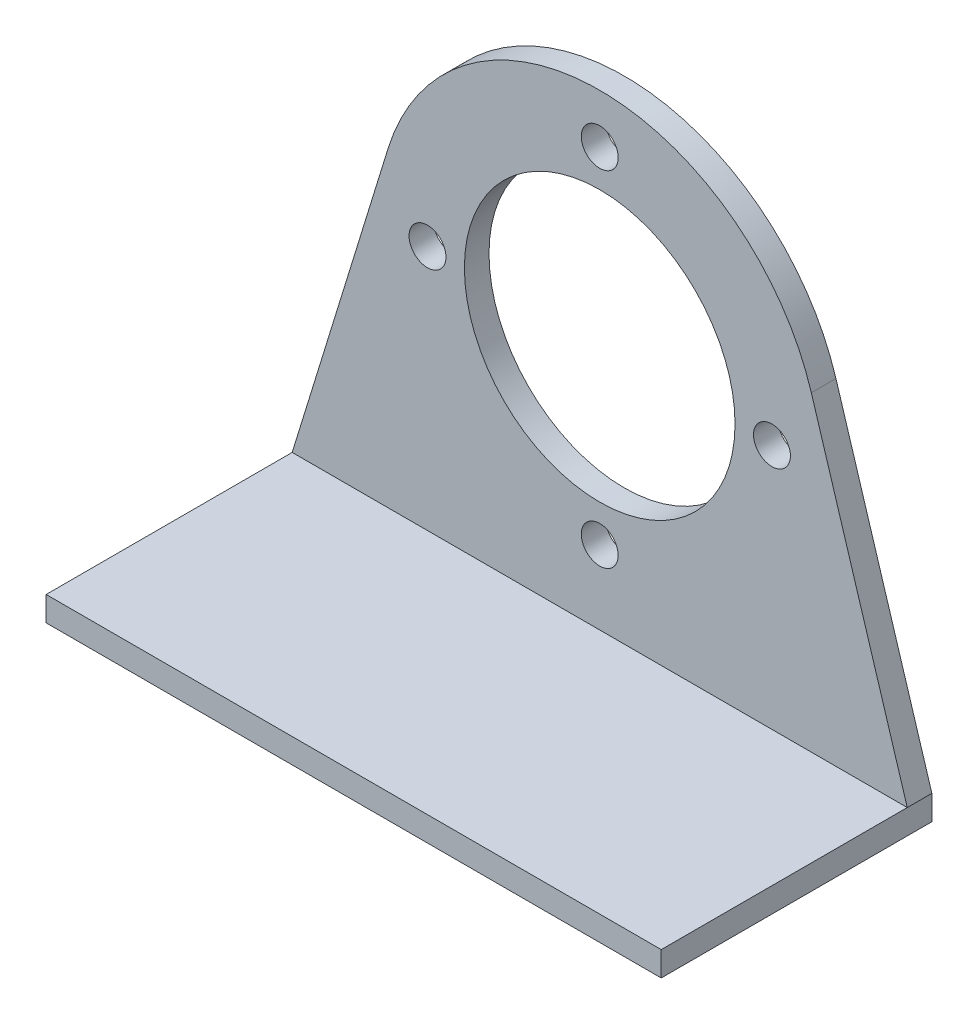
SolidWorks part; units mm, degrees
ref_plane "Front Plane" through (0, 0, 0) normal (0, 0, 1) x (1, 0, 0)
ref_plane "Top Plane" through (0, 0, 0) normal (0, 1, 0) x (1, 0, 0)
ref_plane "Right Plane" through (0, 0, 0) normal (1, 0, 0) x (0, 0, -1)
sketch "Sketch1" plane through (0, 0, 0) normal (0, 0, 1) x (1, 0, 0)
  line L0 (-25, -20) -> (25, -20)
  line L1 (-17.2015, 5.3018) -> (-25, -20)
  line L2 (17.2015, 5.3018) -> (25, -20)
  circle A0 centre (0, 0) radius 11
  circle A1 centre (0, 14) radius 1.5
  circle A2 centre (14, 0) radius 1.5
  circle A3 centre (0, -14) radius 1.5
  circle A4 centre (-14, 0) radius 1.5
  arc A6 (-17.2015, 5.3018) -> (17.2015, 5.3018) centre (0, 0) cw
  point P7 (0, -20)
  point P14 (0, 0)
  point P17 (0, 0)
  point P18 (0, 0)
  dimension "D1" = 22
  dimension "D4" = 3
  dimension "D5" = 18
  dimension "D2" = 14
  dimension "D6" = 50
  dimension "D7" = 20
  dimension "D3" = 4
extrude "Boss-Extrude1" add sketch "Sketch1" along normal blind 2
sketch "Sketch2" plane through (0, 0, 2) normal (0, 0, 1) x (1, 0, 0)
  line L1 (-25, -20) -> (25, -20)
  line L2 (-25, -20) -> (-25, -22)
  line L3 (-25, -22) -> (25, -22)
  line L4 (25, -20) -> (25, -22)
  point P5 (25, -20)
  dimension "D1" = 2
extrude "Boss-Extrude2" add sketch "Sketch2" along normal blind 20 and the other way blind 2
